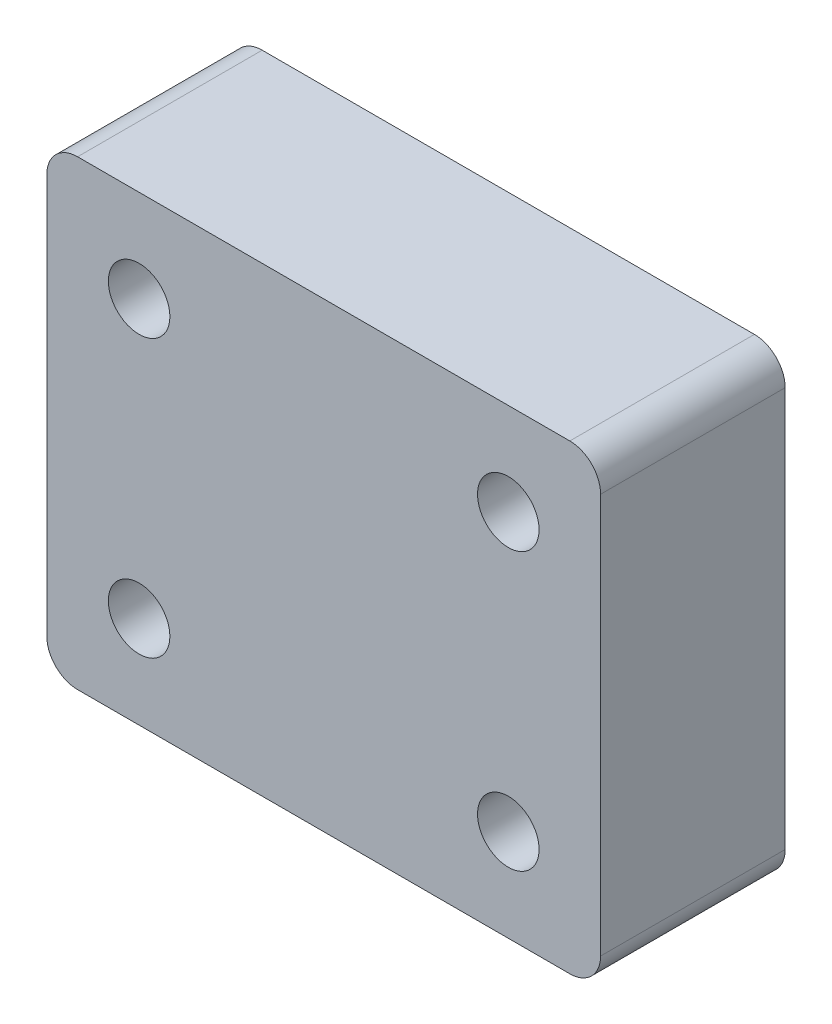
SolidWorks part; units mm, degrees
ref_plane "Płaszczyzna przednia" through (0, 0, 0) normal (0, 0, 1) x (1, 0, 0)
ref_plane "Płaszczyzna górna" through (0, 0, 0) normal (0, 1, 0) x (1, 0, 0)
ref_plane "Płaszczyzna prawa" through (0, 0, 0) normal (1, 0, 0) x (0, 0, -1)
sketch "Szkic1" plane through (0, 0, 0) normal (0, 0, 1) x (1, 0, 0)
  line L1 (-1, 0) -> (35, 0)
  line L2 (-1, 0) -> (-1, 30)
  line L3 (-1, 30) -> (35, 30)
  line L4 (35, 0) -> (35, 30)
extrude "Dodanie-wyciągnięcie1" add sketch "Szkic1" along normal blind 12
sketch "Szkic2" plane through (0, 0, 12) normal (0, 0, 1) x (1, 0, 0)
  circle A0 centre (5, 6) radius 2
  circle A1 centre (29, 6) radius 2
  circle A2 centre (29, 24) radius 2
  circle A3 centre (5, 24) radius 2
extrude "Wytnij-wyciągnięcie1" cut sketch "Szkic2" against normal blind 12
fillet "Zaokrąglenie1" radius 2 4 edges at (-1, 0, 6) (-1, 30, 6) (35, 0, 6) (35, 30, 6)
